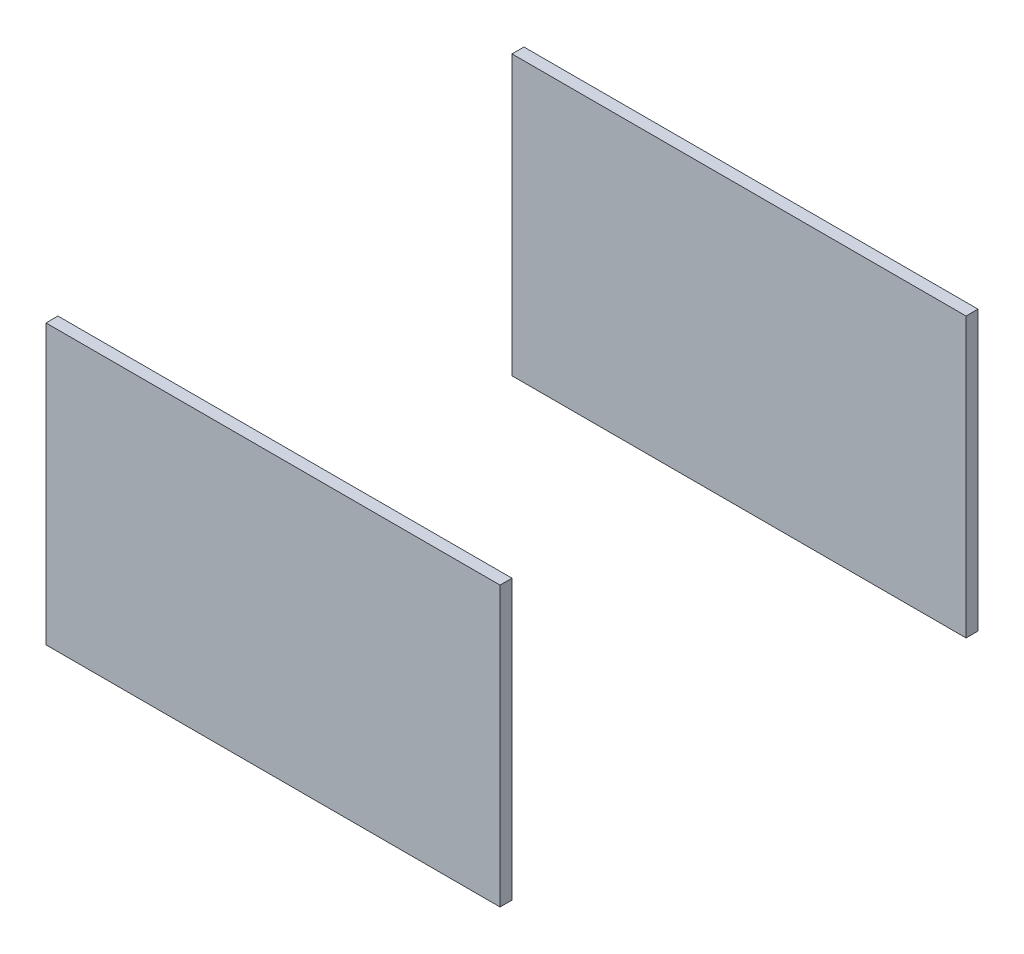
SolidWorks part; units mm, degrees
ref_plane "Front Plane" through (0, 0, 0) normal (0, 0, 1) x (1, 0, 0)
ref_plane "Top Plane" through (0, 0, 0) normal (0, 1, 0) x (1, 0, 0)
ref_plane "Right Plane" through (0, 0, 0) normal (1, 0, 0) x (0, 0, -1)
sketch "Sketch1" plane through (0, 0, 0) normal (0, 1, 0) x (1, 0, 0)
  line L1 (-70, -80) -> (70, -80)
  line L2 (-70, -80) -> (-70, 80)
  line L3 (-70, 80) -> (70, 80)
  line L4 (70, -80) -> (70, 80)
  line L5 (-70, -80) -> (70, 80) construction
  line L6 (-70, 80) -> (70, -80) construction
  point P0 (0, 0)
  dimension "D1" = 140
  dimension "D2" = 160
extrude "Boss-Extrude1" add sketch "Sketch1" along normal blind 3
sketch "Sketch2" plane through (0, 3, 0) normal (0, 1, 0) x (1, 0, 0)
  line L1 (-57, -57) -> (57, -57)
  line L2 (-57, -57) -> (-57, 57)
  line L3 (-57, 57) -> (57, 57)
  line L4 (57, -57) -> (57, 57)
  line L5 (-57, -57) -> (57, 57) construction
  line L6 (-57, 57) -> (57, -57) construction
  line L7 (60, -60) -> (-60, -60)
  line L8 (60, -60) -> (60, 60)
  line L9 (60, 60) -> (-60, 60)
  line L10 (-60, -60) -> (-60, 60)
  line L11 (60, -60) -> (-60, 60) construction
  line L12 (60, 60) -> (-60, -60) construction
  point P0 (0, 0)
  point P6 (0, 0)
  dimension "D1" = 114
  dimension "D2" = 114
  dimension "D3" = 120
extrude "Boss-Extrude2" add sketch "Sketch2" along normal blind 70
sketch "Sketch4" plane through (0, 73, 0) normal (0, 1, 0) x (1, 0, 0)
  line L1 (-60, 60) -> (60, 60)
  line L2 (-60, 60) -> (-60, -60)
  line L3 (-60, -60) -> (60, -60)
  line L4 (60, 60) -> (60, -60)
  dimension "D1" = 120
  dimension "D2" = 120
extrude "Boss-Extrude4" add sketch "Sketch4" along normal blind 3
sketch "Sketch5" plane through (0, 76, 0) normal (0, 1, 0) x (1, 0, 0)
  line L0 (-60, 60) -> (60, -60) construction
  line L1 (-10.27, -9.855) -> (29.63, -9.855)
  line L2 (-10.27, -9.855) -> (-10.27, 9.855)
  line L3 (-10.27, 9.855) -> (29.63, 9.855)
  line L4 (29.63, -9.855) -> (29.63, 9.855)
  line L5 (-10.27, -9.855) -> (29.63, 9.855) construction
  line L6 (-10.27, 9.855) -> (29.63, -9.855) construction
  line L7 (60, -60) -> (60, 60) construction
  line L8 (60, -60) -> (60, 60) construction
  line L9 (60, -60) -> (60, 60) construction
  line L10 (60, 60) -> (-60, 60) construction
  line L11 (60, 60) -> (-60, -60) construction
  circle A1 centre (34.39, -4.925) radius 2.1
  circle A2 centre (34.39, 4.925) radius 2.1
  circle A4 centre (-15.03, -4.925) radius 2.1
  circle A5 centre (-15.03, 4.925) radius 2.1
  point P3 (9.68, 0)
  dimension "D2" = 4.2
  dimension "D6" = 9.85
  dimension "D7" = 4.93
  dimension "D8" = 4.93
  dimension "D9" = 4.93
  dimension "D10" = 9.68
  dimension "D11" = 4.93
  dimension "D12" = 4.93
  dimension "D1" = 39.9
  dimension "D3" = 19.71
  dimension "D4" = 4.76
  dimension "D5" = 4.76
extrude "Cut-Extrude2" cut sketch "Sketch5" against normal blind 3
sketch "Sketch6" plane through (0, 76, 0) normal (0, 1, 0) x (1, 0, 0)
  line L1 (9.1491, -8.655) -> (-9.1491, -8.655)
  line L2 (9.1491, -8.655) -> (9.1491, 8.655)
  line L3 (9.1491, 8.655) -> (-9.1491, 8.655)
  line L4 (-9.1491, -8.655) -> (-9.1491, 8.655)
  line L5 (9.1491, -8.655) -> (-9.1491, 8.655) construction
  line L6 (9.1491, 8.655) -> (-9.1491, -8.655) construction
  point P0 (0, 0)
extrude "Cut-Extrude3" cut sketch "Sketch6" against normal blind 3
sketch "Sketch7" plane through (0, 0, 0) normal (0, 1, 0) x (1, 0, 0)
  line L1 (-45, -45) -> (45, -45)
  line L2 (-45, -45) -> (-45, 45)
  line L3 (-45, 45) -> (45, 45)
  line L4 (45, -45) -> (45, 45)
  line L5 (-45, -45) -> (45, 45) construction
  line L6 (-45, 45) -> (45, -45) construction
  point P0 (0, 0)
  dimension "D1" = 90
  dimension "D2" = 90
sketch "Sketch13" plane through (0, 76, 0) normal (0, 1, 0) x (1, 0, 0)
  arc A0 (-3.7926, 43.0768) -> (-0.8101, -42.9734) centre (-3.7926, 0) ccw construction
  arc A1 (-3.7926, 49.7288) -> (-0.3495, -49.6094) centre (-3.7926, 0) ccw
  arc A2 (-3.7926, 36.4249) -> (-1.2706, -36.3375) centre (-3.7926, 0) ccw
  arc A3 (-3.7926, 36.4249) -> (-3.7926, 49.7288) centre (-3.7926, 43.0768) ccw
  arc A4 (-0.3495, -49.6094) -> (-1.2706, -36.3375) centre (-0.8101, -42.9734) ccw
  point P3 (-46.8436, -1.4922)
extrude "Cut-Extrude8" cut sketch "Sketch13" against normal blind 5
sketch "Sketch15" plane through (0, 3, 0) normal (0, 1, 0) x (1, 0, 0)
  line L0 (70, 80) -> (-70, 80) construction
  line L1 (90, 80) -> (-169.0216, 80)
  line L2 (90, 80) -> (90, -100.2694)
  line L3 (90, -100.2694) -> (-169.0216, -100.2694)
  line L4 (-169.0216, 80) -> (-169.0216, -100.2694)
extrude "Boss-Extrude5" add sketch "Sketch15" against normal blind 3
sketch "Sketch18" plane through (0, 3, 0) normal (0, 1, 0) x (1, 0, 0)
  circle A0 centre (-55.452, -27.2274) radius 1.6 construction
  circle A1 centre (-55.452, -27.2274) radius 1.6
  circle A2 centre (-55.452, 32.2086) radius 1.6 construction
  circle A3 centre (-55.452, 32.2086) radius 1.6
  circle A4 centre (4.746, 32.2086) radius 1.6 construction
  circle A5 centre (4.746, 32.2086) radius 1.6
  circle A6 centre (4.746, -27.2274) radius 1.6 construction
  circle A7 centre (4.746, -27.2274) radius 1.6
extrude "Cut-Extrude9" cut sketch "Sketch18" against normal blind 10
sketch "Sketch19" plane through (-60, 0, 0) normal (-1, 0, 0) x (0, 0, 1)
  line L0 (12.3674, 3) -> (12.3674, 33) construction
  line L1 (-60, 3) -> (60, 3) construction
  line L2 (-5.6466, 31.35) -> (-5.6466, 26.9) construction
  line L3 (6.3674, 30.75) -> (18.3674, 30.75)
  line L4 (6.3674, 30.75) -> (6.3674, 35.25)
  line L5 (6.3674, 35.25) -> (18.3674, 35.25)
  line L6 (18.3674, 30.75) -> (18.3674, 35.25)
  line L7 (6.3674, 30.75) -> (18.3674, 35.25) construction
  line L8 (6.3674, 35.25) -> (18.3674, 30.75) construction
  line L9 (-5.2594, 33) -> (-5.2594, 41.4) construction
  line L10 (-5.2594, 33) -> (-17.2594, 33) construction
  line L11 (-5.2594, 41.4) -> (-17.2594, 41.4) construction
  line L12 (-17.2594, 33) -> (-17.2594, 41.4) construction
  line L13 (-33.6488, 33.0619) -> (-23.5648, 33.0619) construction
  line L14 (-28.1126, 38.85) -> (-28.1126, 27.45) construction
  line L15 (-23.5648, 40.424) -> (-23.5648, 33.0619) construction
  line L16 (-33.6488, 40.424) -> (-23.5648, 40.424) construction
  line L17 (-33.6488, 40.424) -> (-33.6488, 33.0619) construction
  line L18 (-5.2594, 33) -> (-5.2594, 41.4)
  line L19 (-5.2594, 33) -> (-17.2594, 33)
  line L20 (-5.2594, 41.4) -> (-17.2594, 41.4)
  line L21 (-17.2594, 33) -> (-17.2594, 41.4)
  line L22 (-33.6488, 33.0619) -> (-23.5648, 33.0619)
  line L23 (-28.1126, 38.85) -> (-28.1126, 27.45)
  line L24 (-23.5648, 40.424) -> (-23.5648, 33.0619)
  line L25 (-33.6488, 40.424) -> (-23.5648, 40.424)
  line L26 (-33.6488, 40.424) -> (-33.6488, 33.0619)
  dimension "D1" = 14.86
  dimension "D2" = 30
  dimension "D3" = 4.5
  dimension "D4" = 90
  dimension "D5" = 12
extrude "Cut-Extrude11" cut sketch "Sketch19" against normal blind 5
sketch "Sketch20" plane through (0, 0, 60) normal (0, 0, 1) x (1, 0, 0)
  line L0 (60, 76) -> (60, 3) construction
  line L1 (-169.0216, 3) -> (94.8999, 3)
  line L2 (-169.0216, 3) -> (-169.0216, -16.6306)
  line L3 (-169.0216, -16.6306) -> (94.8999, -16.6306)
  line L4 (94.8999, 3) -> (94.8999, -16.6306)
  line L5 (-60, 76) -> (60, 76)
  line L6 (-60, 76) -> (-60, 73)
  line L7 (-60, 73) -> (60, 73)
  line L8 (60, 76) -> (60, 73)
  dimension "D1" = 3
extrude "Cut-Extrude12" cut sketch "Sketch20" against normal through all
sketch "Sketch21" plane through (0, 3, 0) normal (0, 1, 0) x (1, 0, 0)
  line L1 (-169.0216, -60) -> (90, -60)
  line L2 (-169.0216, -60) -> (-169.0216, -100.2694)
  line L3 (-169.0216, -100.2694) -> (90, -100.2694)
  line L4 (90, -60) -> (90, -100.2694)
extrude "Cut-Extrude13" cut sketch "Sketch21" against normal through all
sketch "Sketch22" plane through (0, 73, 0) normal (0, 1, 0) x (1, 0, 0)
  line L0 (-60, -60) -> (60, -60) construction
  line L1 (-60, 60) -> (-57, 60)
  line L2 (-60, 60) -> (-60, -60)
  line L3 (-60, -60) -> (-57, -60)
  line L4 (-57, 60) -> (-57, -60)
  line L6 (60, 60) -> (57, 60)
  line L7 (60, 60) -> (60, -62.072)
  line L8 (60, -62.072) -> (57, -62.072)
  line L9 (57, 60) -> (57, -62.072)
  dimension "D1" = 3
  dimension "D2" = 3
extrude "Cut-Extrude14" cut sketch "Sketch22" against normal through all
